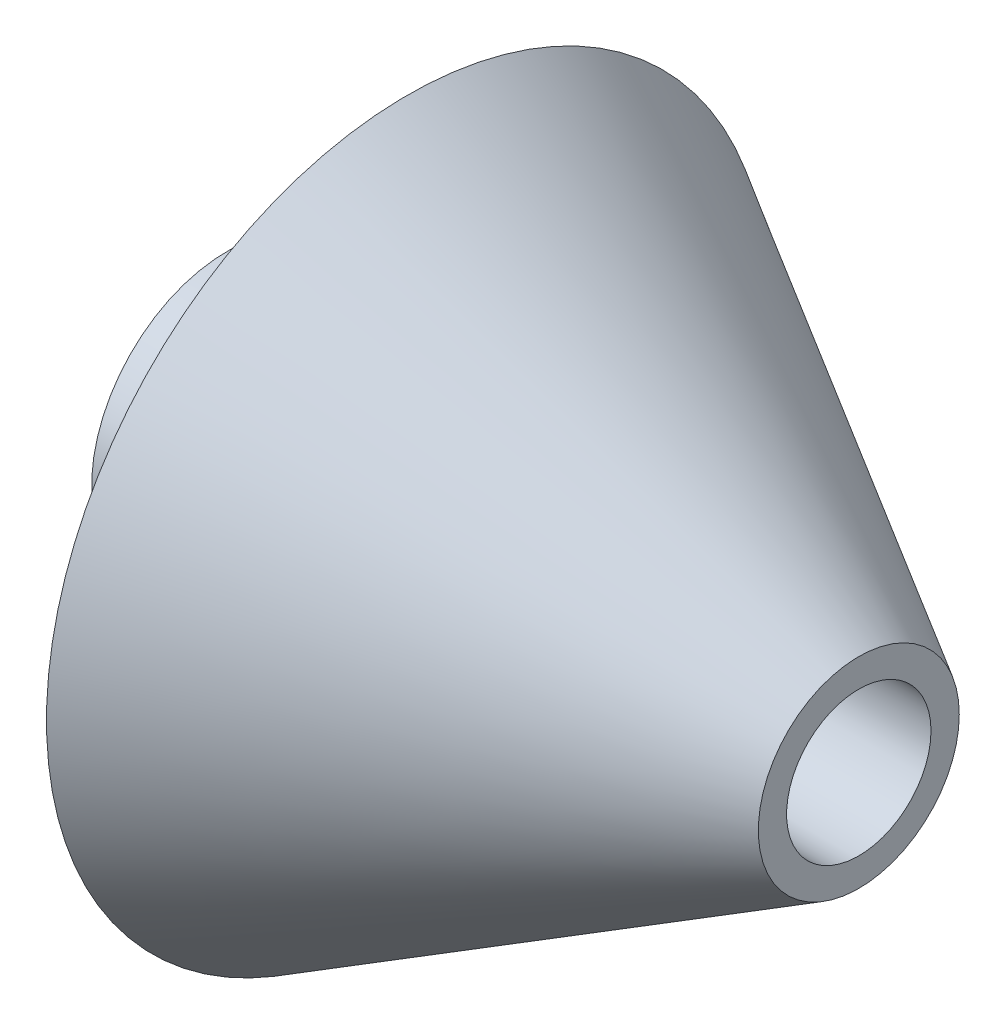
SolidWorks part; units mm, degrees
ref_plane "Alzado" through (0, 0, 0) normal (0, 0, 1) x (1, 0, 0)
ref_plane "Planta" through (0, 0, 0) normal (0, 1, 0) x (1, 0, 0)
ref_plane "Vista lateral" through (0, 0, 0) normal (1, 0, 0) x (0, 0, -1)
sketch "Croquis1" plane through (0, 0, 0) normal (1, 0, 0) x (0, 0, -1)
  line L0 (0, 7.5) -> (0, -7.5) construction
  line L1 (-7.5, 0) -> (7.5, 0) construction
  circle A0 centre (0, 0) radius 7.5
  dimension "D1" = 15
extrude "Saliente-Extruir1" add sketch "Croquis1" along normal blind 10
sketch "Croquis2" plane through (10, 0, 0) normal (1, 0, 0) x (0, 0, -1)
  circle A0 centre (0, 0) radius 20
  dimension "D1" = 40
extrude "Saliente-Extruir2" add sketch "Croquis2" along normal blind 25 draft 30
sketch "Croquis3" plane through (35, 0, 0) normal (1, 0, 0) x (0, 0, -1)
  circle A0 centre (0, 0) radius 4
  dimension "D1" = 8
extrude "Cortar-Extruir2" cut sketch "Croquis3" against normal blind 70
hole_wizard "Taladro de margen para M41" positions "Croquis3D1" profile "Croquis4" hole size "M4" standard "ISO"
sketch3d "Croquis3D1"
  point P0 (5, 7.4812, -0.5307)
  dimension "D1" = 5
sketch "Croquis4" plane through (5, 7.4812, -0.5307) normal (1, 0, 0) x (0, 0.0708, 0.9975)
  line L0 (0, 0) -> (0, 3.5)
  line L1 (0, 3.5) -> (2.25, 3.5)
  line L2 (2.25, 3.5) -> (2.25, 0)
  line L5 (2.25, 0) -> (0, 0)
  line L11 (0, -6.35) -> (0, 107.95) construction
  dimension "Diámetro de taladro hasta el siguiente" = 4.5
  dimension "Profundidad de taladro hasta el siguiente" = 3.5
